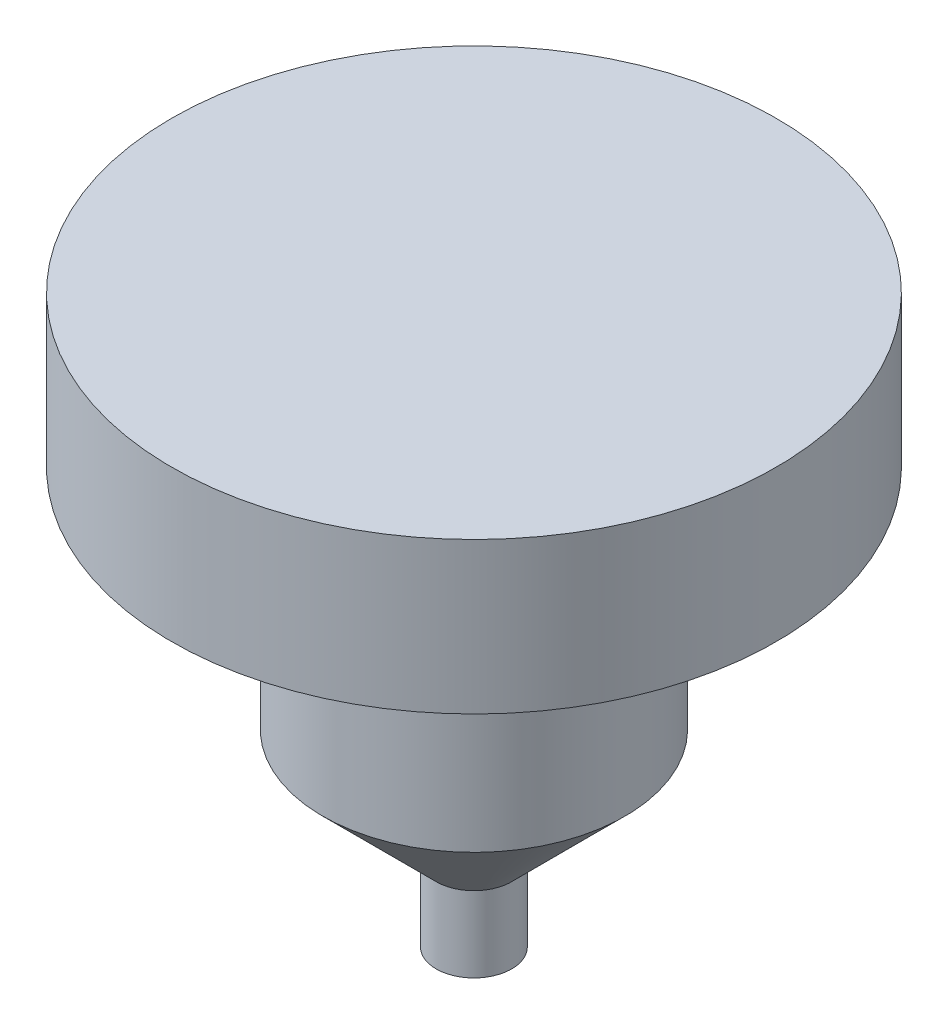
SolidWorks part; units mm, degrees
ref_plane "Front Plane" through (0, 0, 0) normal (0, 0, 1) x (1, 0, 0)
ref_plane "Top Plane" through (0, 0, 0) normal (0, 1, 0) x (1, 0, 0)
ref_plane "Right Plane" through (0, 0, 0) normal (1, 0, 0) x (0, 0, -1)
sketch "Sketch1" plane through (0, 0, 0) normal (0, 0, 1) x (1, 0, 0)
  line L0 (0, 0) -> (1, 0)
  line L1 (1, 0) -> (5, 2.3094)
  line L2 (5, 2.3094) -> (5, 12.3094)
  line L3 (5, 12.3094) -> (20, 27.3094)
  line L4 (20, 27.3094) -> (20, 57.3094)
  line L5 (40, 77.3094) -> (0, 77.3094)
  line L6 (0, 77.3094) -> (0, 0)
  line L7 (20, 57.3094) -> (40, 57.3094)
  line L8 (40, 57.3094) -> (40, 77.3094)
  dimension "D3" = 20
  dimension "D4" = 45
  dimension "D1" = 60
  dimension "D2" = 5
  dimension "D5" = 40
  dimension "D6" = 10
  dimension "D7" = 1
  dimension "D8" = 20
  dimension "D9" = 30
revolve "Revolve1" add sketch "Sketch1" angle 360 about L6
